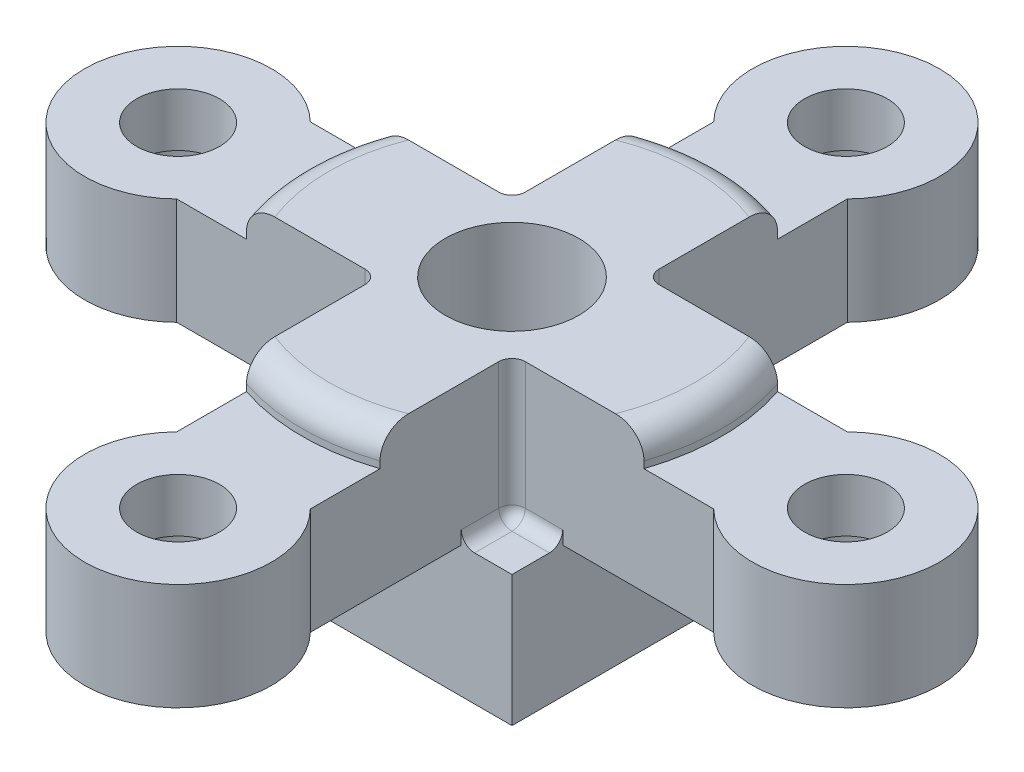
SolidWorks part; units mm, degrees
material "Nylon 6/10"
ref_plane "Front Plane" through (0, 0, 0) normal (0, 0, 1) x (1, 0, 0)
ref_plane "Top Plane" through (0, 0, 0) normal (0, 1, 0) x (1, 0, 0)
ref_plane "Right Plane" through (0, 0, 0) normal (1, 0, 0) x (0, 0, -1)
sketch "Sketch1" plane through (0, 0, 0) normal (0, 1, 0) x (1, 0, 0)
  line L0 (-5, 5) -> (-5, 25)
  line L1 (-25, -5) -> (-5, -5)
  line L2 (-25, -5) -> (-25, 5)
  line L3 (-25, 5) -> (-5, 5)
  line L4 (25, -5) -> (25, 5)
  line L5 (-25, -5) -> (25, 5) construction
  line L6 (-25, 5) -> (25, -5) construction
  line L7 (-5, -25) -> (5, -25)
  line L8 (-5, -25) -> (-5, -5)
  line L9 (-5, 25) -> (5, 25)
  line L10 (5, -25) -> (5, -5)
  line L11 (-5, -25) -> (5, 25) construction
  line L12 (-5, 25) -> (5, -25) construction
  line L13 (5, 5) -> (25, 5)
  line L14 (5, 5) -> (5, 25)
  line L15 (5, -5) -> (25, -5)
  point P0 (0, 0)
  point P6 (0, 0)
  dimension "D1" = 10
  dimension "D2" = 10
  dimension "D3" = 50
  dimension "D4" = 50
extrude "Boss-Extrude1" add sketch "Sketch1" along normal blind 8
sketch "Sketch2" plane through (0, 8, 0) normal (0, 1, 0) x (1, 0, 0)
  line L0 (25, -5) -> (25, 5) construction
  circle A0 centre (25, 0) radius 7
  circle A1 centre (0, -25) radius 7
  circle A2 centre (-25, 0) radius 7
  circle A3 centre (0, 25) radius 7
  point P13 (0, 0)
  dimension "D1" = 14
  dimension "D2" = 4
extrude "Boss-Extrude2" add sketch "Sketch2" against normal up to surface (8 mm away) up to face at (0, 0, 0)
sketch "Sketch3" plane through (0, 8, 0) normal (0, 1, 0) x (1, 0, 0)
  circle A0 centre (25, 0) radius 3.1
  circle A1 centre (0, -25) radius 3.1
  circle A2 centre (-25, 0) radius 3.1
  circle A3 centre (0, 25) radius 3.1
  point P12 (0, 0)
  dimension "D1" = 6.2
  dimension "D2" = 4
extrude "Cut-Extrude1" cut sketch "Sketch3" against normal up to surface (8 mm away) up to face at (0, 0, 0)
sketch "Sketch4" plane through (0, 0, 0) normal (0, 1, 0) x (1, 0, 0)
  circle A0 centre (25, 0) radius 5.05
  circle A1 centre (0, -25) radius 5.05
  circle A2 centre (-25, 0) radius 5.05
  circle A3 centre (0, 25) radius 5.05
  point P12 (0, 0)
  dimension "D1" = 10.1
  dimension "D2" = 4
extrude "Cut-Extrude4" cut sketch "Sketch4" along normal blind 4
sketch "Sketch5" plane through (0, 8, 0) normal (0, 1, 0) x (1, 0, 0)
  line L8 (5, 5) -> (5, 20.101)
  line L9 (-5, 20.101) -> (-5, 5)
  line L10 (-5, 5) -> (-20.101, 5)
  line L11 (-20.101, -5) -> (-5, -5)
  line L12 (-5, -5) -> (-5, -20.101)
  line L13 (5, -20.101) -> (5, -5)
  line L14 (5, -5) -> (20.101, -5)
  line L15 (20.101, 5) -> (5, 5)
  line L16 (5, 5) -> (5, 14.8825)
  line L17 (-5, 14.8825) -> (-5, 5)
  line L18 (-5, 5) -> (-14.8825, 5)
  line L19 (-14.8825, -5) -> (-5, -5)
  line L20 (-5, -5) -> (-5, -14.8825)
  line L21 (5, -14.8825) -> (5, -5)
  line L22 (5, -5) -> (14.8825, -5)
  line L23 (14.8825, 5) -> (5, 5)
  arc A0 (-14.8825, 5) -> (-14.8825, -5) centre (0, 0) ccw
  arc A1 (5, 14.8825) -> (-5, 14.8825) centre (0, 0) ccw
  arc A2 (14.8825, -5) -> (14.8825, 5) centre (0, 0) ccw
  arc A3 (-5, -14.8825) -> (5, -14.8825) centre (0, 0) ccw
  arc A5 (5, 20.101) -> (-5, 20.101) centre (0, 25) ccw
  arc A6 (-20.101, 5) -> (-20.101, -5) centre (-25, 0) ccw
  arc A7 (-5, -20.101) -> (5, -20.101) centre (0, -25) ccw
  arc A8 (20.101, -5) -> (20.101, 5) centre (25, 0) ccw
  dimension "D1" = 31.4
  dimension "D2" = 0
extrude "Boss-Extrude3" add sketch "Sketch5" along normal blind 2.5
sketch "Sketch6" plane through (0, 0, 0) normal (0, -1, 0) x (1, 0, 0)
  line L1 (-8.8, -8.8) -> (8.8, -8.8)
  line L2 (-8.8, -8.8) -> (-8.8, 8.8)
  line L3 (-8.8, 8.8) -> (8.8, 8.8)
  line L4 (8.8, -8.8) -> (8.8, 8.8)
  line L5 (-8.8, -8.8) -> (8.8, 8.8) construction
  line L6 (-8.8, 8.8) -> (8.8, -8.8) construction
  point P0 (0, 0)
  dimension "D1" = 17.6
  dimension "D2" = 90
extrude "Boss-Extrude4" add sketch "Sketch6" along normal blind 9.8
sketch "Sketch7" plane through (0, 10.5, 0) normal (0, 1, 0) x (1, 0, 0)
  circle A0 centre (0, 0) radius 5
  dimension "D1" = 10
extrude "Cut-Extrude5" cut sketch "Sketch7" against normal up to surface (20.3 mm away) up to face at (0, -9.8, 0)
fillet "Fillet1" radius 2 4 edges at (15.7, 10.5, 0) (0, 10.5, 15.7) (-15.7, 10.5, 0) (0, 10.5, -15.7)
fillet "Fillet3" radius 1 12 edges at (5, 0, -6.9) (5, 5.25, -5) (6.9, 0, -5) (-5, 5.25, -5) (-5, 0, -6.9) (-6.9, 0, -5) (6.9, 0, 5) (5, 0, 6.9) (5, 5.25, 5) (-5, 5.25, 5) (-5, 0, 6.9) (-6.9, 0, 5)
equation "\"D3@Sketch2\"= 50 - \"D2@Sketch2\""
